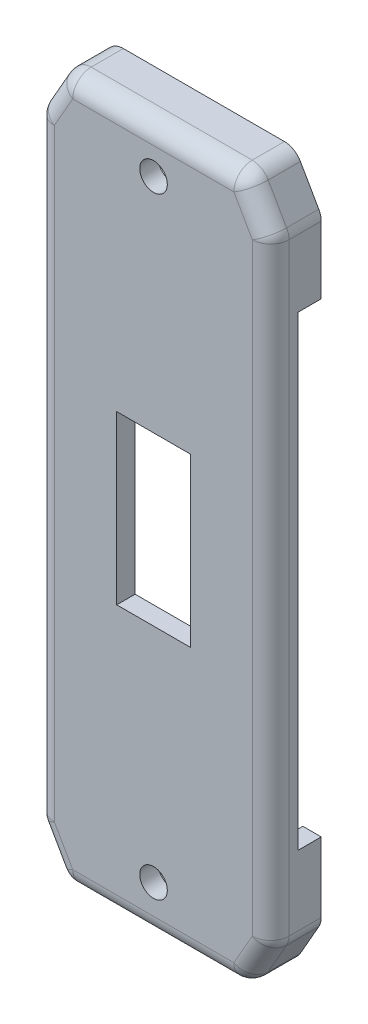
SolidWorks part; units mm, degrees
ref_plane "Front Plane" through (0, 0, 0) normal (0, 0, 1) x (1, 0, 0)
ref_plane "Top Plane" through (0, 0, 0) normal (0, 1, 0) x (1, 0, 0)
ref_plane "Right Plane" through (0, 0, 0) normal (1, 0, 0) x (0, 0, -1)
sketch "Sketch1" plane through (0, 0, 0) normal (0, 0, 1) x (1, 0, 0)
  line L0 (-13.697, 41.4789) -> (-11.157, 45.9239)
  line L5 (11.0935, -34.925) -> (-11.0934, -34.925) construction
  line L6 (11.0935, -34.925) -> (11.0935, 34.925) construction
  line L7 (11.0935, 34.925) -> (-11.0934, 34.925) construction
  line L8 (-11.0934, -34.925) -> (-11.0934, 34.925) construction
  line L9 (11.0935, -34.925) -> (-11.0934, 34.925) construction
  line L10 (11.0935, 34.925) -> (-11.0934, -34.925) construction
  line L11 (11.0998, -46.2781) -> (-11.157, -46.2781)
  line L12 (13.6398, -41.8331) -> (13.6398, 41.4789)
  line L13 (11.0998, 45.9239) -> (-11.157, 45.9239)
  line L14 (-13.697, -41.8331) -> (-13.697, 41.4789)
  line L15 (13.6398, -45.7323) -> (-13.697, 45.9239) construction
  line L16 (13.6398, 45.9239) -> (-13.6969, -46.1163) construction
  line L17 (13.6398, 41.4789) -> (11.0998, 45.9239)
  line L18 (13.6398, -41.8331) -> (11.0998, -46.2781)
  line L19 (-13.697, -41.8331) -> (-11.157, -46.2781)
  line L20 (-16.237, 42.1534) -> (-12.631, 48.4639)
  line L21 (12.5738, -48.8181) -> (-12.631, -48.8181)
  line L22 (16.1798, -42.5076) -> (16.1798, 42.1534)
  line L23 (12.5738, 48.4639) -> (-12.631, 48.4639)
  line L24 (-16.237, -42.5076) -> (-16.237, 42.1534)
  line L25 (16.1798, 42.1534) -> (12.5738, 48.4639)
  line L26 (16.1798, -42.5076) -> (12.5738, -48.8181)
  line L27 (-16.237, -42.5076) -> (-12.631, -48.8181)
  circle A0 centre (1.1263, 42.1139) radius 1.7145 construction
  circle A1 centre (0, -42.2275) radius 1.7145 construction
  point P0 (0, 0)
  point P6 (0, 0)
  dimension "D8" = 3.429
  dimension "D1" = 22.1869
  dimension "D2" = 69.85
  dimension "D3" = 92.202
  dimension "D4" = 2.5464
  dimension "D5" = 2.54
  dimension "D6" = 4.445
  dimension "D7" = 3.81
  dimension "D9" = 2.6035
  dimension "D10" = 2.54
  dimension "D11" = 2.54
  dimension "D12" = 2.54
  dimension "D13" = 2.54
  dimension "D14" = 2.54
  dimension "D15" = 2.54
extrude "Boss-Extrude1" add sketch "Sketch1" along normal blind 4.445
sketch "Sketch2" plane through (0, 0, 4.445) normal (0, 0, 1) x (1, 0, 0)
  line L0 (-16.237, 42.1534) -> (-16.237, -42.5076) construction
  line L1 (-16.237, -42.5076) -> (-12.631, -48.8181) construction
  line L2 (-12.631, -48.8181) -> (12.5738, -48.8181) construction
  line L3 (12.5738, -48.8181) -> (16.1798, -42.5076) construction
  line L4 (16.1798, -42.5076) -> (16.1798, 42.1534) construction
  line L5 (16.1798, 42.1534) -> (12.5738, 48.4639) construction
  line L6 (12.5738, 48.4639) -> (-12.631, 48.4639) construction
  line L7 (-12.631, 48.4639) -> (-16.237, 42.1534) construction
  line L8 (-16.237, 42.1534) -> (-16.237, -42.5076)
  line L9 (-16.237, -42.5076) -> (-12.631, -48.8181)
  line L10 (-12.631, -48.8181) -> (12.5738, -48.8181)
  line L11 (12.5738, -48.8181) -> (16.1798, -42.5076)
  line L12 (16.1798, -42.5076) -> (16.1798, 42.1534)
  line L13 (16.1798, 42.1534) -> (12.5738, 48.4639)
  line L14 (12.5738, 48.4639) -> (-12.631, 48.4639)
  line L15 (-12.631, 48.4639) -> (-16.237, 42.1534)
  line L16 (0, -46.0375) -> (0, 46.0375) construction
  line L18 (5.08, -11.557) -> (-5.08, -11.557)
  line L19 (5.08, -11.557) -> (5.08, 11.557)
  line L20 (5.08, 11.557) -> (-5.08, 11.557)
  line L21 (-5.08, -11.557) -> (-5.08, 11.557)
  line L22 (5.08, -11.557) -> (-5.08, 11.557) construction
  line L23 (5.08, 11.557) -> (-5.08, -11.557) construction
  circle A0 centre (0, 42.2275) radius 1.905
  circle A1 centre (0, -42.2275) radius 1.905
  point P15 (0, 0)
  point P20 (0, 0)
  dimension "D4" = 3.81
  dimension "D5" = 3.81
  dimension "D1" = 92.075
  dimension "D2" = 3.81
  dimension "D3" = 3.81
  dimension "D6" = 23.114
  dimension "D7" = 10.16
extrude "Boss-Extrude2" add sketch "Sketch2" along normal blind 2.54
fillet "Fillet1" radius 2.54 16 edges at (-0.0286, 48.4639, 6.985) (14.3768, 45.3087, 6.985) (16.1798, -0.1771, 6.985) (14.3768, -45.6629, 6.985) (-0.0286, -48.8181, 6.985) (-14.434, -45.6629, 6.985) (-16.237, -0.1771, 6.985) (-14.434, 45.3087, 6.985) (-16.237, -42.5076, 3.4925) (-12.631, -48.8181, 3.4925) (12.5738, -48.8181, 3.4925) (16.1798, -42.5076, 3.4925) (16.1798, 42.1534, 3.4925) (12.5738, 48.4639, 3.4925) (-16.237, 42.1534, 3.4925) (-12.631, 48.4639, 3.4925)
sketch "Sketch3" plane through (16.1798, 0, 0) normal (1, 0, 0) x (0, 0, -1)
  line L0 (0, -41.8331) -> (0, 41.4789) construction
  line L1 (3.2004, -32.1818) -> (-3.2004, -32.1818)
  line L2 (3.2004, -32.1818) -> (3.2004, 32.1818)
  line L3 (3.2004, 32.1818) -> (-3.2004, 32.1818)
  line L4 (-3.2004, -32.1818) -> (-3.2004, 32.1818)
  line L5 (3.2004, -32.1818) -> (-3.2004, 32.1818) construction
  line L6 (3.2004, 32.1818) -> (-3.2004, -32.1818) construction
  point P0 (0, 0)
  dimension "D1" = 64.3636
  dimension "D2" = 3.2004
extrude "Cut-Extrude1" cut sketch "Sketch3" against normal up to surface (2.54 mm away) up to face at (13.6398, -0.1771, 2.2225)
